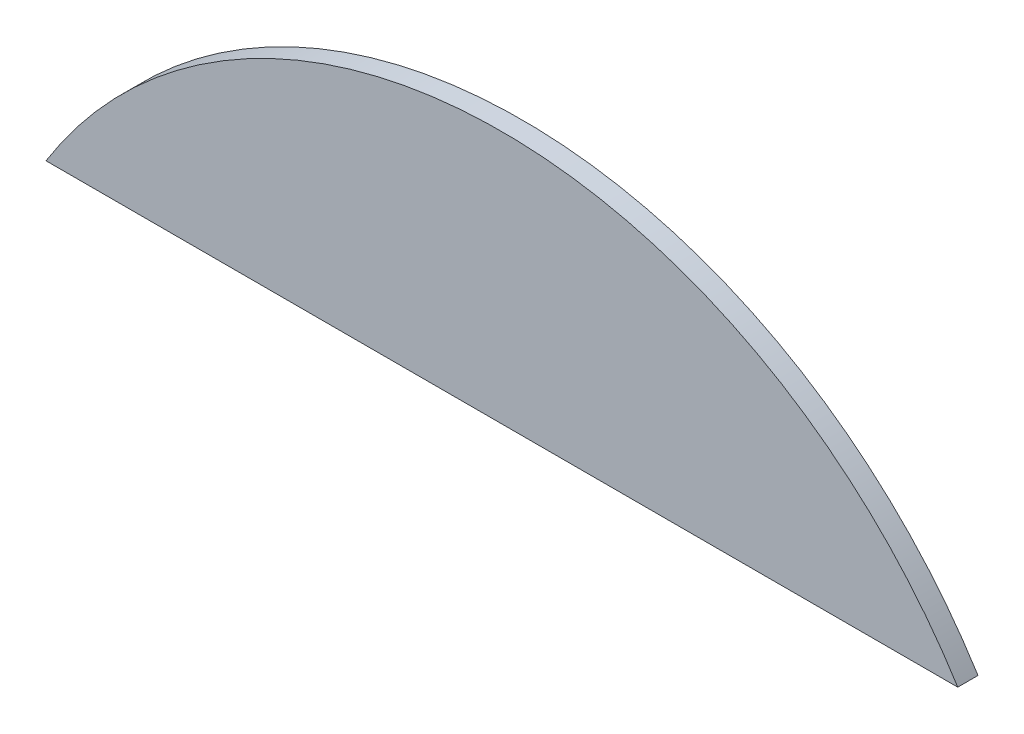
SolidWorks part; units mm, degrees
ref_plane "Front Plane" through (0, 0, 0) normal (0, 0, 1) x (1, 0, 0)
ref_plane "Top Plane" through (0, 0, 0) normal (0, 1, 0) x (1, 0, 0)
ref_plane "Right Plane" through (0, 0, 0) normal (1, 0, 0) x (0, 0, -1)
sketch "Sketch1" plane through (0, 0, 0) normal (0, 0, 1) x (1, 0, 0)
  line L0 (-45, 0) -> (45, 0)
  arc A0 (-45, 0) -> (45, 0) centre (0, -28) cw
  point P4 (0, 0)
  point P6 (0, 25)
  dimension "D2" = 25
  dimension "D1" = 90
extrude "Boss-Extrude1" add sketch "Sketch1" along normal mid plane 2
